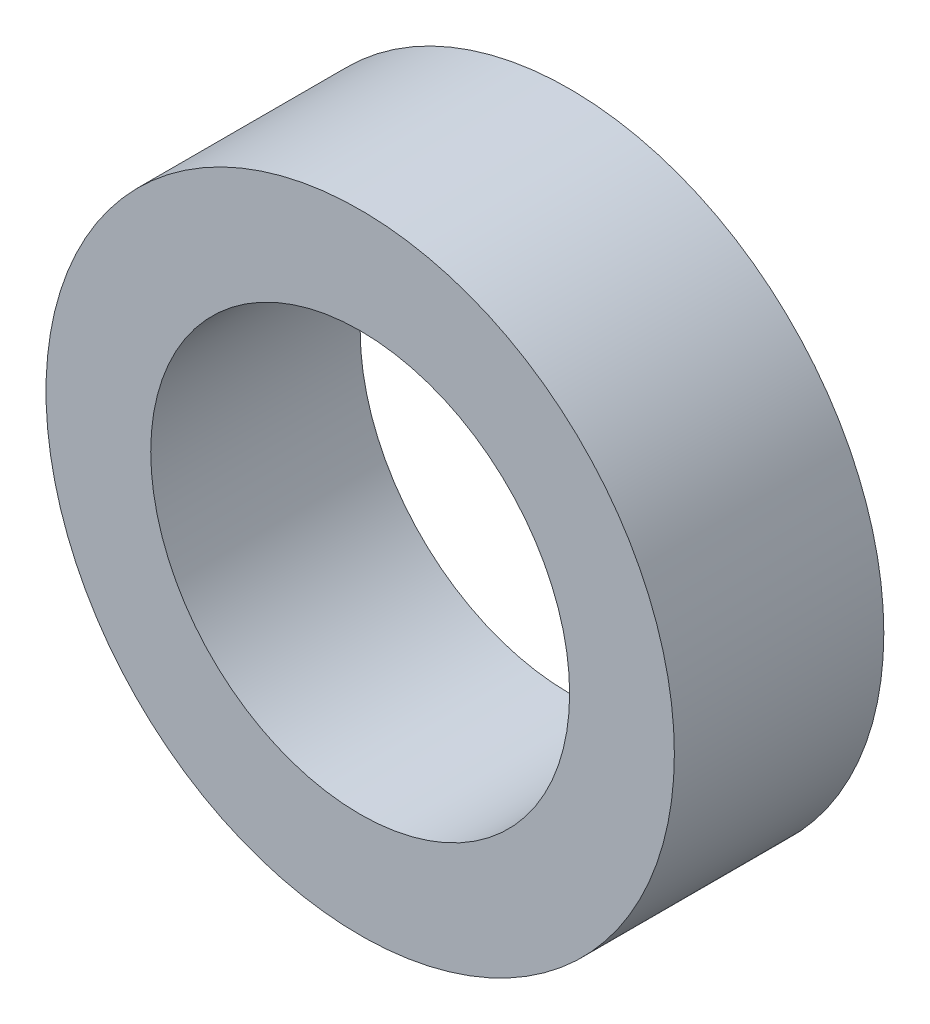
SolidWorks part; units mm, degrees
ref_plane "Front Plane" through (0, 0, 0) normal (0, 0, 1) x (1, 0, 0)
ref_plane "Top Plane" through (0, 0, 0) normal (0, 1, 0) x (1, 0, 0)
ref_plane "Right Plane" through (0, 0, 0) normal (1, 0, 0) x (0, 0, -1)
sketch "Sketch1" plane through (0, 0, 0) normal (0, 0, 1) x (1, 0, 0)
  circle A0 centre (0, 0) radius 4
  dimension "D1" = 8
extrude "Extrude-Thin1" add sketch "Sketch1" along normal blind 4 thin
